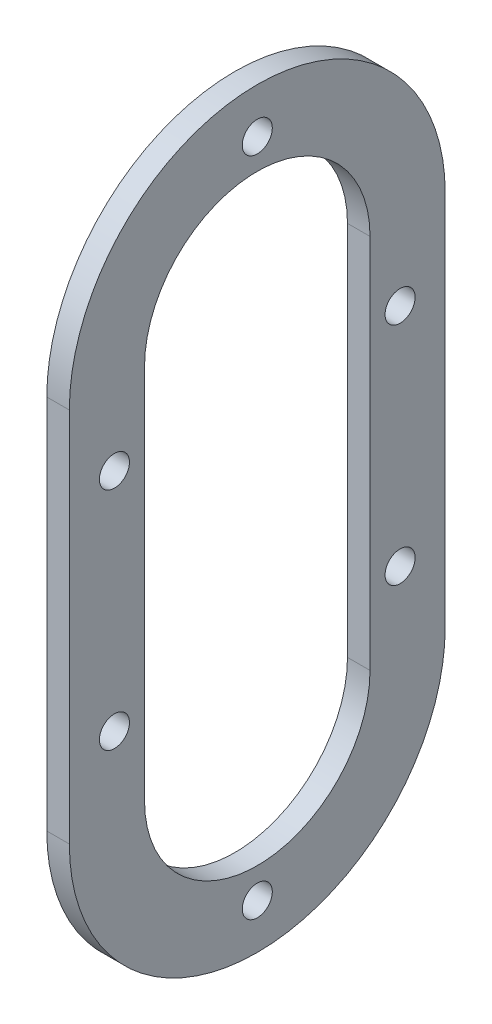
SolidWorks part; units mm, degrees
material "1060 Alloy"
ref_plane "Front Plane" through (0, 0, 0) normal (1, 0, 0) x (0, 1, 0)
ref_plane "Top Plane" through (0, 0, 0) normal (0, 0, 1) x (0, 1, 0)
ref_plane "Right Plane" through (0, 0, 0) normal (0, 1, 0) x (-1, 0, 0)
sketch "Sketch1" plane through (0, 0, 0) normal (1, 0, 0) x (0, 1, 0)
  line L0 (0, 0) -> (50, 0) construction
  line L1 (0, 25) -> (50, 25)
  line L2 (0, -25) -> (50, -25)
  line L3 (0, 15) -> (50, 15)
  line L4 (0, -15) -> (50, -15)
  arc A0 (0, 25) -> (0, -25) centre (0, 0) ccw
  arc A1 (50, -25) -> (50, 25) centre (50, 0) ccw
  arc A2 (50, -15) -> (50, 15) centre (50, 0) ccw
  arc A3 (0, 15) -> (0, -15) centre (0, 0) ccw
  circle A4 centre (10, 19) radius 2
  circle A5 centre (40, 19) radius 2
  circle A6 centre (69, 0) radius 2
  circle A7 centre (-19, 0) radius 2
  circle A8 centre (10, -19) radius 2
  circle A9 centre (40, -19) radius 2
  point P3 (25, 0)
  point P26 (-25, 0)
  point P27 (75, 0)
  dimension "D2" = 25
  dimension "D4" = 4
  dimension "D1" = 50
  dimension "D5" = 6
  dimension "D6" = 6
  dimension "D7" = 6
  dimension "D8" = 6
  dimension "D9" = 10
  dimension "D10" = 10
  dimension "D11" = 25
  dimension "D12" = 6
  dimension "D3" = 10
extrude "Boss-Extrude1" add sketch "Sketch1" along normal blind 3
